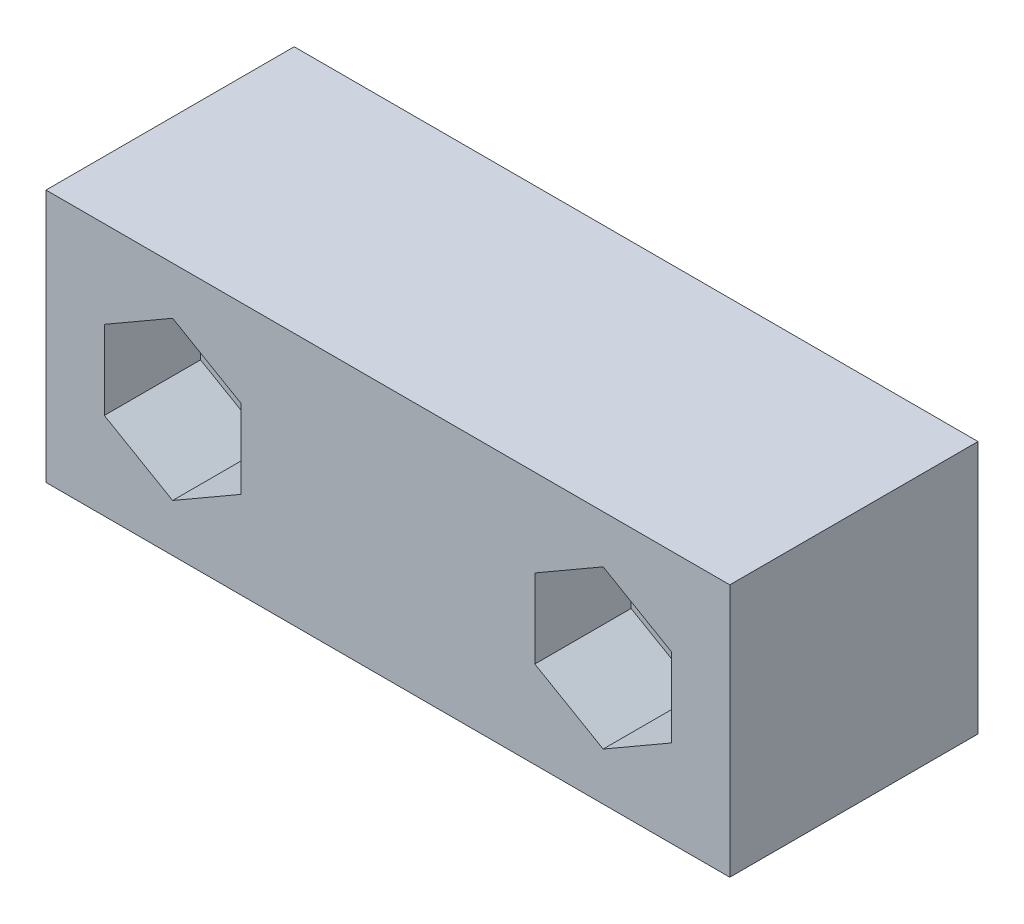
SolidWorks part; units mm, degrees
ref_plane "Front Plane" through (0, 0, 0) normal (0, 0, 1) x (1, 0, 0)
ref_plane "Top Plane" through (0, 0, 0) normal (0, 1, 0) x (1, 0, 0)
ref_plane "Right Plane" through (0, 0, 0) normal (1, 0, 0) x (0, 0, -1)
ref_plane "Plane1" through (0, 0, 0) normal (0, 0, -1) x (-1, 0, 0)
sketch "Sketch1" plane through (0, 0, 0) normal (0, 0, -1) x (-1, 0, 0)
  line L0 (5, -5) -> (5, 5)
  line L1 (5, 5) -> (-22, 5)
  line L2 (-22, 5) -> (-22, -5)
  line L3 (-22, -5) -> (5, -5)
extrude "Boss-Extrude1" add sketch "Sketch1" against normal blind 9.8
sketch "Sketch2" plane through (0, 0, 9.8) normal (0, 0, 1) x (1, 0, 0)
  line L0 (-2.6981, -1.5577) -> (0, -3.1155)
  line L1 (0, -3.1155) -> (2.6981, -1.5577)
  line L2 (2.6981, -1.5577) -> (2.6981, 1.5577)
  line L3 (2.6981, 1.5577) -> (0, 3.1155)
  line L4 (0, 3.1155) -> (-2.6981, 1.5577)
  line L5 (-2.6981, 1.5577) -> (-2.6981, -1.5577)
extrude "Cut-Extrude1" cut sketch "Sketch2" against normal blind 3.8
sketch "Sketch3" plane through (0, 0, 9.8) normal (0, 0, 1) x (1, 0, 0)
  line L0 (14.3019, -1.5577) -> (17, -3.1155)
  line L1 (17, -3.1155) -> (19.6981, -1.5577)
  line L2 (19.6981, -1.5577) -> (19.6981, 1.5577)
  line L3 (19.6981, 1.5577) -> (17, 3.1155)
  line L4 (17, 3.1155) -> (14.3019, 1.5577)
  line L5 (14.3019, 1.5577) -> (14.3019, -1.5577)
extrude "Cut-Extrude2" cut sketch "Sketch3" against normal blind 3.8
hole_wizard "Hole1" positions "Sketch5" profile "Sketch4" legacy
sketch "Sketch5" plane through (0, 0, 0) normal (0, 0, -1) x (-1, 0, 0)
  point P0 (0, 0)
sketch "Sketch4" plane through (0, 0, 0) normal (1, 0, 0) x (0, 1, 0)
  line L0 (0, 0) -> (0, 9.8)
  line L1 (0, 9.8) -> (1.7, 9.8)
  line L2 (1.7, 9.8) -> (1.7, 0)
  line L3 (1.7, 0) -> (0, 0)
  line L4 (0, 110) -> (0, -10) construction
  dimension "Diameter" = 3.4
  dimension "Depth" = 9.8
hole_wizard "Hole2" positions "Sketch7" profile "Sketch6" legacy
sketch "Sketch7" plane through (0, 0, 0) normal (0, 0, -1) x (-1, 0, 0)
  point P0 (-17, 0)
sketch "Sketch6" plane through (17, 0, 0) normal (1, 0, 0) x (0, 1, 0)
  line L0 (0, 0) -> (0, 9.8)
  line L1 (0, 9.8) -> (1.7, 9.8)
  line L2 (1.7, 9.8) -> (1.7, 0)
  line L3 (1.7, 0) -> (0, 0)
  line L4 (0, 110) -> (0, -10) construction
  dimension "Diameter" = 3.4
  dimension "Depth" = 9.8
